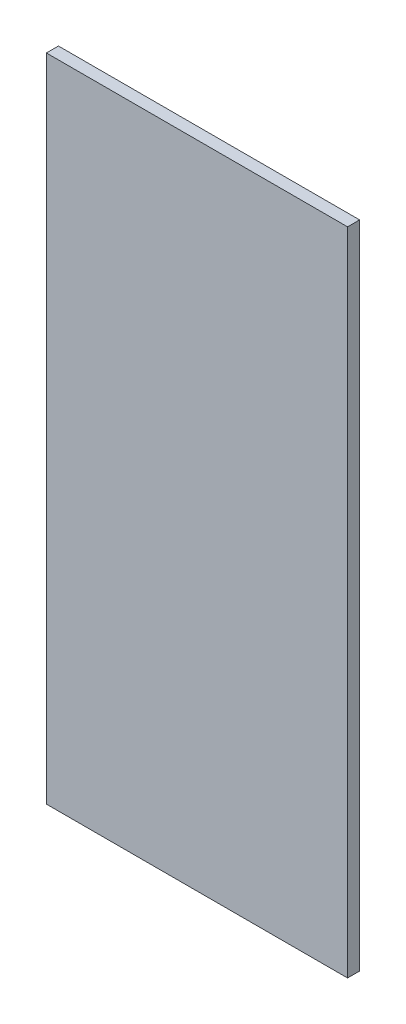
SolidWorks part; units mm, degrees
ref_plane "Front Plane" through (0, 0, 0) normal (0, 0, 1) x (1, 0, 0)
ref_plane "Top Plane" through (0, 0, 0) normal (0, 1, 0) x (1, 0, 0)
ref_plane "Right Plane" through (0, 0, 0) normal (1, 0, 0) x (0, 0, -1)
sketch "Sketch1" plane through (0, 0, 0) normal (0, 0, 1) x (1, 0, 0)
  line L1 (0, 0) -> (125, 0)
  line L2 (0, 0) -> (0, -270)
  line L3 (0, -270) -> (125, -270)
  line L4 (125, 0) -> (125, -270)
  dimension "D1" = 125
  dimension "D2" = 270
extrude "Boss-Extrude1" add sketch "Sketch1" along normal blind 5
